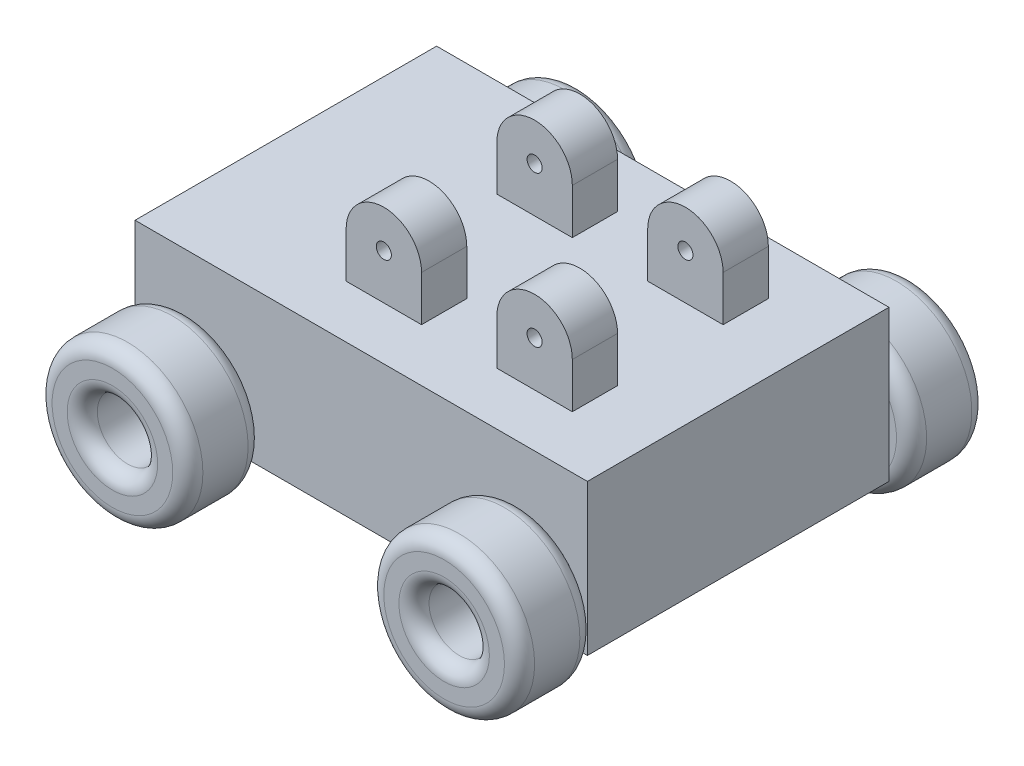
SolidWorks part; units mm, degrees
ref_plane "Front Plane" through (0, 0, 0) normal (0, 0, 1) x (1, 0, 0)
ref_plane "Top Plane" through (0, 0, 0) normal (0, 1, 0) x (1, 0, 0)
ref_plane "Right Plane" through (0, 0, 0) normal (1, 0, 0) x (0, 0, -1)
sketch "Sketch3" plane through (0, 0, 0) normal (0, 1, 0) x (1, 0, 0)
  line L1 (-150, 100) -> (150, 100)
  line L2 (-150, 100) -> (-150, -100)
  line L3 (-150, -100) -> (150, -100)
  line L4 (150, 100) -> (150, -100)
  line L5 (-150, 100) -> (150, -100) construction
  line L6 (-150, -100) -> (150, 100) construction
  point P0 (0, 0)
  dimension "D1" = 300
  dimension "D2" = 200
extrude "Boss-Extrude1" add sketch "Sketch3" along normal blind 100 contours L1 L4 L3 L2
sketch "Sketch4" plane through (0, 0, 100) normal (0, 0, 1) x (1, 0, 0)
  circle A0 centre (-110, 22.5) radius 20
  circle A1 centre (110, 22.5) radius 20
extrude "Cut-Extrude1" cut sketch "Sketch4" along normal blind 200 from vertex at -200 starting at point (150, 0, -100)
ref_plane "Plane1" through (0, 0, 0) normal (0, 0, 1) x (1, 0, 0)
sketch "Sketch6" plane through (0, 0, 0) normal (0, 0, 1) x (1, 0, 0)
  circle A0 centre (-110, 22.5) radius 20
  circle A1 centre (110, 22.5) radius 20
extrude "Boss-Extrude2" add sketch "Sketch6" against normal blind 120 and the other way blind 120
sketch "Sketch7" plane through (0, 100, 0) normal (0, 1, 0) x (1, 0, 0)
  line L1 (-45, -35) -> (5, -35)
  line L2 (-45, -35) -> (-45, -65)
  line L3 (-45, -65) -> (5, -65)
  line L4 (5, -35) -> (5, -65)
  line L5 (-45, -35) -> (5, -65) construction
  line L6 (-45, -65) -> (5, -35) construction
  line L7 (-45, 65) -> (5, 65)
  line L8 (-45, 65) -> (-45, 35)
  line L9 (-45, 35) -> (5, 35)
  line L10 (5, 65) -> (5, 35)
  line L11 (-45, 65) -> (5, 35) construction
  line L12 (-45, 35) -> (5, 65) construction
  line L14 (0, 0) -> (0, 88.5917) construction
  line L16 (0, 88.5917) -> (0, -87.3632) construction
  line L17 (0, 0) -> (87.2718, 0) construction
  line L18 (87.2718, 0) -> (-121.0725, 0) construction
  point P0 (-20, -50)
  point P5 (-20, 50)
  dimension "D1" = 20
  dimension "D2" = 50
  dimension "D3" = 30
  dimension "D4" = 30
  dimension "D5" = 50
  dimension "D6" = 50
  dimension "D7" = 50
sketch "Sketch8" plane through (0, 100, 0) normal (0, 1, 0) x (1, 0, 0)
extrude "Boss-Extrude3" add sketch "Sketch7" along normal blind 30
sketch "Sketch9" plane through (0, 0, 65) normal (0, 0, 1) x (1, 0, 0)
  line L0 (-45, 130) -> (5, 130) construction
  circle A0 centre (-20, 130) radius 25
extrude "Boss-Extrude6" add sketch "Sketch9" against normal blind 30 contours A0
mirror "Mirror1" about plane through (0, 0, 0) normal (0, 0, 1) of "Boss-Extrude6"
sketch "Sketch11" plane through (0, 0, 65) normal (0, 0, 1) x (1, 0, 0)
  circle A0 centre (-20, 130) radius 5
extrude "Cut-Extrude2" cut sketch "Sketch11" against normal blind 186 from surface at 0 starting at face at (-20, 121.25, 65)
sketch "Sketch13" plane through (0, 0, 120) normal (0, 0, 1) x (1, 0, 0)
  circle A0 centre (-110, 22.5) radius 50
  circle A1 centre (110, 22.5) radius 50
extrude "Boss-Extrude7" add sketch "Sketch13" along normal blind 35 and the other way blind 15
sketch "Sketch14" plane through (0, 0, 155) normal (0, 0, 1) x (1, 0, 0)
  circle A0 centre (-110, 22.5) radius 20
  circle A1 centre (110, 22.5) radius 20
extrude "Cut-Extrude3" cut sketch "Sketch14" against normal blind 35
fillet "Fillet3" radius 10 5 edges at (160, 22.5, 155) (130, 22.5, 155) (160, 22.5, 105) (-60, 22.5, 105) (-60, 22.5, 155)
fillet "Fillet4" radius 10 1 edges at (-90, 22.5, 155)
mirror "Mirror4" about plane through (0, 0, 0) normal (0, 0, 1) of "Fillet4", "Fillet3", "Boss-Extrude7", "Cut-Extrude3", "Cut-Extrude2"
sketch "Sketch17" plane through (0, 0, 65) normal (0, 0, 1) x (1, 0, 0)
  circle A0 centre (-20, 130) radius 5
ref_plane "Plane2" through (0, 0, 0) normal (-1, 0, 0) x (0, 0, 1)
sketch "Sketch18" plane through (0, 100, 0) normal (0, 1, 0) x (1, 0, 0)
  line L0 (0, 85.558) -> (0, -89.2664) construction
  line L1 (0, 55) -> (0, -55) construction
  line L2 (120.9156, 0) -> (-105.8248, 0) construction
  line L3 (55, -65) -> (105, -35) construction
  line L4 (55, 65) -> (105, 65)
  line L5 (55, 65) -> (55, 35)
  line L6 (55, 35) -> (105, 35)
  line L7 (105, 65) -> (105, 35)
  line L8 (55, 65) -> (105, 35) construction
  line L9 (55, 35) -> (105, 65) construction
  line L10 (55, -35) -> (105, -65) construction
  line L11 (55, -35) -> (105, -35)
  line L12 (105, -65) -> (105, -35)
  line L13 (55, -65) -> (105, -65)
  line L14 (55, -65) -> (55, -35)
  point P7 (80, 50)
  dimension "D1" = 50
  dimension "D2" = 30
  dimension "D3" = 80
  dimension "D4" = 50
extrude "Boss-Extrude10" add sketch "Sketch18" along normal blind 30
sketch "Sketch19" plane through (0, 0, 65) normal (0, 0, 1) x (1, 0, 0)
  line L0 (55, 130) -> (105, 130) construction
  circle A0 centre (80, 130) radius 25
extrude "Boss-Extrude11" add sketch "Sketch19" against normal blind 30
sketch "Sketch20" plane through (0, 0, -65) normal (0, 0, -1) x (-1, 0, 0)
  line L0 (-105, 130) -> (-55, 130) construction
  circle A0 centre (-80, 130) radius 25
extrude "Boss-Extrude12" add sketch "Sketch20" against normal blind 30
sketch "Sketch22" plane through (0, 0, 65) normal (0, 0, 1) x (1, 0, 0)
  circle A0 centre (80, 130) radius 5
extrude "Cut-Extrude4" cut sketch "Sketch22" against normal blind 145 and the other way blind 15
sketch "Sketch23" plane through (0, 0, -65) normal (0, 0, -1) x (-1, 0, 0)
  circle A0 centre (-80, 130) radius 5
  point P3 (0, 0)
sketch "Sketch24" plane through (0, 0, -65) normal (0, 0, -1) x (-1, 0, 0)
  circle A0 centre (-80, 130) radius 5
